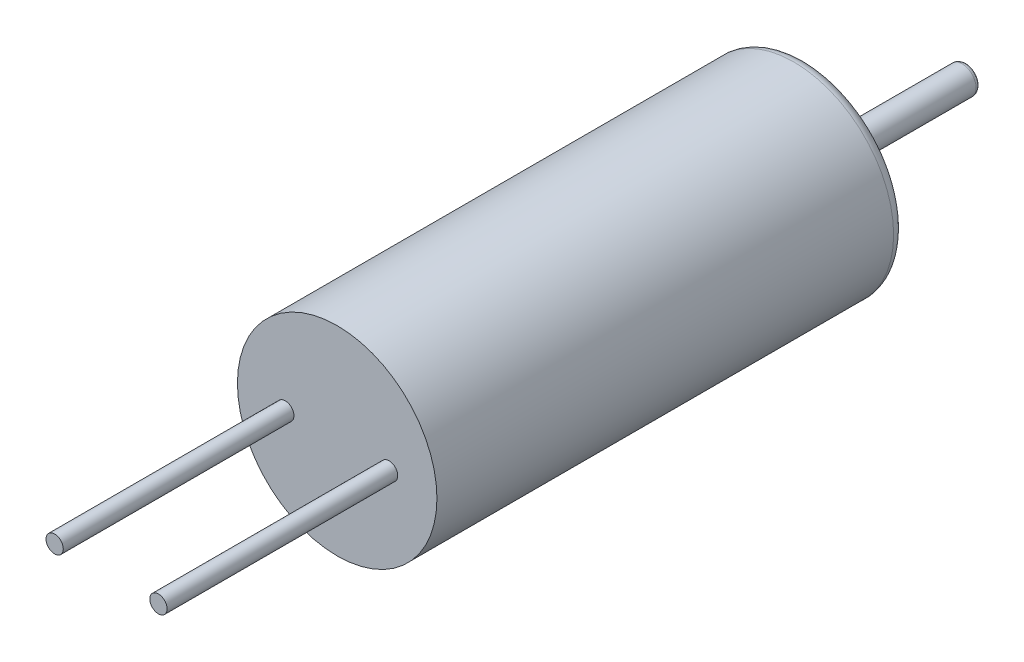
SolidWorks part; units mm, degrees
ref_plane "Front Plane" through (0, 0, 0) normal (0, 0, 1) x (1, 0, 0)
ref_plane "Top Plane" through (0, 0, 0) normal (0, 1, 0) x (1, 0, 0)
ref_plane "Right Plane" through (0, 0, 0) normal (1, 0, 0) x (0, 0, -1)
sketch "Sketch1" plane through (0, 0, 0) normal (0, 1, 0) x (1, 0, 0)
  line L1 (4.325, 20.3) -> (4.325, 0)
  line L2 (4.325, 0) -> (0, 0)
  line L3 (0, 0) -> (0, 27.3)
  line L4 (0, 27.3) -> (0.6, 27.3)
  line L6 (0.6, 27.3) -> (0.6, 21.1)
  line L7 (0.6, 21.1) -> (1.2, 21.1)
  line L8 (1.2, 21.1) -> (1.2, 20.3)
  line L9 (1.2, 20.3) -> (4.325, 20.3)
  point P8 (-0.6, 27.3)
  point P9 (-4.325, 20.3)
  point P12 (-1.2, 21.1)
  dimension "D1" = 8.65
  dimension "D2" = 2.4
  dimension "D3" = 1.2
  dimension "D4" = 20.3
  dimension "D5" = 0.8
  dimension "D6" = 27.3
revolve "Revolve1" add sketch "Sketch1" angle 360 about L3
fillet "Fillet1" radius 0.5 1 edges at (4.325, 0, -20.3)
fillet "Fillet2" radius 0.2 2 edges at (0.6, 0, -27.3) (1.2, 0, -21.1)
sketch "Sketch2" plane through (0, 0, 0) normal (0, 0, 1) x (1, 0, 0)
  line L0 (-2.25, 0) -> (0, 0) construction
  line L1 (0, 0) -> (0, 4.325) construction
  circle A0 centre (-2.25, 0) radius 0.375
  circle A1 centre (0, 0) radius 4.325 construction
  circle A2 centre (2.25, 0) radius 0.375
  point P2 (0, 4.325)
  dimension "D2" = 0.75
  dimension "D1" = 4.5
extrude "Boss-Extrude1" add sketch "Sketch2" along normal blind 10
